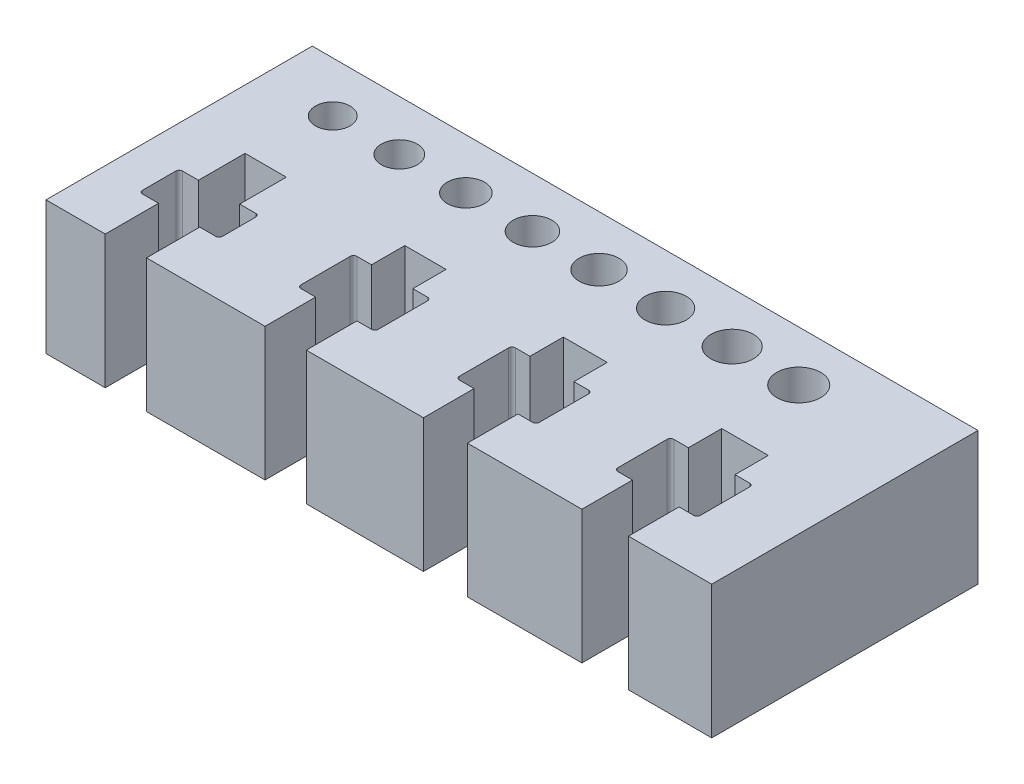
SolidWorks part; units mm, degrees
ref_plane "Front Plane" through (0, 0, 0) normal (0, 0, 1) x (1, 0, 0)
ref_plane "Top Plane" through (0, 0, 0) normal (0, 1, 0) x (1, 0, 0)
ref_plane "Right Plane" through (0, 0, 0) normal (1, 0, 0) x (0, 0, -1)
sketch "Sketch2" plane through (0, 0, 0) normal (0, 1, 0) x (1, 0, 0)
  line L1 (-25, 10) -> (25, 10)
  line L2 (-25, 10) -> (-25, -10)
  line L3 (-25, -10) -> (25, -10)
  line L4 (25, 10) -> (25, -10)
  line L5 (-25, 10) -> (25, -10) construction
  line L6 (-25, -10) -> (25, 10) construction
  point P0 (0, 0)
  dimension "D1" = 50
  dimension "D2" = 20
extrude "Boss-Extrude1" add sketch "Sketch2" along normal blind 10
sketch "Sketch3" plane through (0, 10, 0) normal (0, 1, 0) x (1, 0, 0)
  line L0 (5, -10) -> (5, 0.5) construction
  line L1 (-25, -10) -> (25, -10) construction
  line L2 (6.65, 0.5) -> (3.35, 0.5) construction
  line L3 (3.35, 0.5) -> (3.35, -10) construction
  line L4 (6.65, -10) -> (3.35, -10)
  line L5 (3.35, -10) -> (3.35, -6.2)
  line L6 (3.35, -6.2) -> (2.25, -6.2)
  line L7 (2, -5.95) -> (2, -2.25)
  line L8 (2.25, -2) -> (3.35, -2)
  line L9 (3.35, -2) -> (3.35, 0.5)
  line L10 (3.35, 0.5) -> (6.65, 0.5)
  line L11 (-25, 10) -> (-25, -10) construction
  line L12 (6.65, 0.5) -> (6.65, -10) construction
  line L13 (6.65, -2) -> (6.65, 0.5)
  line L14 (7.75, -2) -> (6.65, -2)
  line L15 (8, -5.95) -> (8, -2.25)
  line L16 (6.65, -6.2) -> (7.75, -6.2)
  line L17 (6.65, -10) -> (6.65, -6.2)
  line L18 (17, -10) -> (17, 0.5) construction
  line L19 (15.25, 0.5) -> (18.75, 0.5)
  line L20 (15.25, 0.5) -> (15.25, -10) construction
  line L21 (15.25, -10) -> (18.75, -10)
  line L22 (15.25, -10) -> (15.25, -6.2)
  line L23 (15.25, -6.2) -> (14.15, -6.2)
  line L24 (13.9, -5.95) -> (13.9, -2.25)
  line L25 (14.15, -2) -> (15.25, -2)
  line L26 (15.25, -2) -> (15.25, 0.5)
  line L27 (18.75, 0.5) -> (18.75, -10) construction
  line L28 (18.75, -2) -> (18.75, 0.5)
  line L29 (19.85, -2) -> (18.75, -2)
  line L30 (20.1, -5.95) -> (20.1, -2.25)
  line L31 (18.75, -6.2) -> (19.85, -6.2)
  line L32 (18.75, -10) -> (18.75, -6.2)
  line L33 (-7, -10) -> (-7, 0.5) construction
  line L34 (-8.55, 0.5) -> (-5.45, 0.5)
  line L35 (-8.55, 0.5) -> (-8.55, -10) construction
  line L36 (-8.55, -10) -> (-5.45, -10)
  line L37 (-8.55, -10) -> (-8.55, -6.2)
  line L38 (-8.55, -6.2) -> (-9.65, -6.2)
  line L39 (-9.9, -5.95) -> (-9.9, -2.25)
  line L40 (-9.65, -2) -> (-8.55, -2)
  line L41 (-8.55, -2) -> (-8.55, 0.5)
  line L42 (-5.45, 0.5) -> (-5.45, -10) construction
  line L43 (-5.45, -2) -> (-5.45, 0.5)
  line L44 (-4.35, -2) -> (-5.45, -2)
  line L45 (-4.1, -5.95) -> (-4.1, -2.25)
  line L46 (-5.45, -6.2) -> (-4.35, -6.2)
  line L47 (-5.45, -10) -> (-5.45, -6.2)
  line L48 (-19, -10) -> (-19, 0.5) construction
  line L49 (-20.55, 0.5) -> (-17.45, 0.5)
  line L50 (-20.55, 0.5) -> (-20.55, -10) construction
  line L51 (-20.55, -10) -> (-17.45, -10)
  line L52 (-20.55, -10) -> (-20.55, -6)
  line L53 (-20.55, -6) -> (-21.75, -6)
  line L54 (-22, -5.75) -> (-22, -3.25)
  line L55 (-21.75, -3) -> (-20.55, -3)
  line L56 (-20.55, -3) -> (-20.55, 0.5)
  line L57 (-17.45, 0.5) -> (-17.45, -10) construction
  line L58 (-17.45, -3) -> (-17.45, 0.5)
  line L59 (-16.25, -3) -> (-17.45, -3)
  line L60 (-16, -5.75) -> (-16, -3.25)
  line L61 (-17.45, -6) -> (-16.25, -6)
  line L62 (-17.45, -10) -> (-17.45, -6)
  line L63 (-25, 6.2223) -> (25, 6.2223) construction
  line L64 (25, -10) -> (25, 10) construction
  arc A0 (2.25, -6.2) -> (2, -5.95) centre (2.25, -5.95) cw
  arc A1 (2, -2.25) -> (2.25, -2) centre (2.25, -2.25) cw
  arc A2 (8, -2.25) -> (7.75, -2) centre (7.75, -2.25) ccw
  arc A3 (7.75, -6.2) -> (8, -5.95) centre (7.75, -5.95) ccw
  arc A4 (14.15, -6.2) -> (13.9, -5.95) centre (14.15, -5.95) cw
  arc A5 (13.9, -2.25) -> (14.15, -2) centre (14.15, -2.25) cw
  arc A6 (20.1, -2.25) -> (19.85, -2) centre (19.85, -2.25) ccw
  arc A7 (19.85, -6.2) -> (20.1, -5.95) centre (19.85, -5.95) ccw
  arc A8 (-9.65, -6.2) -> (-9.9, -5.95) centre (-9.65, -5.95) cw
  arc A9 (-9.9, -2.25) -> (-9.65, -2) centre (-9.65, -2.25) cw
  arc A10 (-4.1, -2.25) -> (-4.35, -2) centre (-4.35, -2.25) ccw
  arc A11 (-4.35, -6.2) -> (-4.1, -5.95) centre (-4.35, -5.95) ccw
  arc A12 (-21.75, -6) -> (-22, -5.75) centre (-21.75, -5.75) cw
  arc A13 (-22, -3.25) -> (-21.75, -3) centre (-21.75, -3.25) cw
  arc A14 (-16, -3.25) -> (-16.25, -3) centre (-16.25, -3.25) ccw
  arc A15 (-16.25, -6) -> (-16, -5.75) centre (-16.25, -5.75) ccw
  circle A16 centre (-19.6857, 6.2223) radius 1.3
  circle A17 centre (-14.6857, 6.2223) radius 1.35
  circle A18 centre (-9.6857, 6.2223) radius 1.4
  circle A19 centre (-4.6857, 6.2223) radius 1.45
  circle A20 centre (0.3143, 6.2223) radius 1.5
  circle A21 centre (5.3143, 6.2223) radius 1.55
  circle A22 centre (10.3143, 6.2223) radius 1.6
  circle A23 centre (15.3143, 6.2223) radius 1.65
  point P14 (2, -6.2)
  point P17 (2, -2)
  point P28 (8, -2)
  point P29 (8, -6.2)
  dimension "D7" = 0.25
  dimension "D10" = 0.25
  dimension "D15" = 0.25
  dimension "D22" = 0.25
  dimension "D30" = 2.6
  dimension "D29" = 2.7
  dimension "D31" = 2.8
  dimension "D32" = 2.9
  dimension "D33" = 3
  dimension "D34" = 3.1
  dimension "D35" = 3.2
  dimension "D36" = 3.3
  dimension "D1" = 10.5
  dimension "D2" = 4.2
  dimension "D3" = 3
  dimension "D4" = 1.65
  dimension "D5" = 30
  dimension "D6" = 8
  dimension "D12" = 12
  dimension "D8" = 1.75
  dimension "D9" = 3.1
  dimension "D11" = 4.2
  dimension "D13" = 8
  dimension "D14" = 10.5
  dimension "D16" = 1.55
  dimension "D17" = 4.2
  dimension "D18" = 10.5
  dimension "D19" = 12
  dimension "D20" = 2.9
  dimension "D21" = 8
  dimension "D23" = 3
  dimension "D24" = 10.5
  dimension "D25" = 3
  dimension "D26" = 7
  dimension "D27" = 1.55
  dimension "D28" = 12
extrude "Cut-Extrude1" cut sketch "Sketch3" against normal through all
equation "\"X-ROD-SPACING\"=45"
equation "\"Y-ROD-SPACING\"=75"
equation "\"Z-ROD-SPACING\"=17.5"
equation "\"Y-BED-OFFSET\"=2"
equation "\"Y-BED-ROD-INSET\"=3.5"
equation "\"Y-BED-SCREW-SPACING\"=209"
equation "\"Y-BED-SCREW-CUTOUT-SLOT-HEIGHT\"=2"
equation "\"T-SLOT-NUT-FILLET-RADIUS\"=0.25"
equation "\"T-SLOT-SCREW-SHAFT-RADIUS\"=1.75"
equation "\"T-SLOT-SCREW-SHAFT-CUTOUT-LENGTH\"=10.5"
equation "\"T-SLOT-NUT-DEPTH\"=4.2"
equation "\"T-SLOT-NUT-WIDTH\"=3"
equation "\"T-SLOT-NUT-END-DISTANCE\"=8"
equation "\"ACRYLIC-THICKNESS\"=10"
equation "\"ACRYLIC-THICKNESS2\"=4.5"
equation "\"ACRYLIC-TAB-CUTOUT-SIZE\"=\"ACRYLIC-THICKNESS\"+\"ACRYLIC-TAB-TOLERANCE\"*2"
equation "\"ACRYLIC-TAB-TOLERANCE\"=.1"
equation "\"ACRYLIC-TAB-WIDTH\"=\"ACRYLIC-THICKNESS\""
equation "\"ACRYLIC-M3-HOLE\"=3.1"
equation "\"SMOOTHROD-CAP-SCREW-DISTANCE\"=20"
equation "\"FRAME-WIDTH-INNER\"=370"
equation "\"NEMA17-HOLE-SPACING\"=31"
equation "\"NEMA17-CENTRAL-CUTOUT\"=22.5"
equation "\"Z-BRACKET-REACH\"=55"
equation "\"Z-ROD-INSET\"=16"
equation "\"TOP-BRACKET-SPACING\"=40"
equation "\"SMOOTHROD-X-LENGTH\"=350"
equation "\"SMOOTHROD-Y-LENGTH\"=350"
equation "\"SMOOTHROD-Z-LENGTH\"=350"
equation "\"SMOOTHROD-TIGHTENING-HEADROOM\"=.25"
equation "\"LEADSCREW-Z-LENGTH\"=300"
equation "\"SCREW-LENGTH-FRAME\"=\"ACRYLIC-THICKNESS\" + 10"
equation "\"SCREW-LENGTH-MOTOR\"=\"ACRYLIC-THICKNESS\" + 5"
equation "\"SCREW-LENGTH-EXTRUDER\"=28"
equation "\"SCREW-HEAD-RADIUS\"=6"
equation "\"PRINTED-M3-HOLE\"=3.5"
equation "\"PRINTED-X-SMOOTHROD-DIAMETER\"=8.2"
equation "\"PRINTED-X-SMOOTHROD-CUTOUT\"=10"
equation "\"PRINTED-X-BASE-HEIGHT\"=10"
equation "\"PRINTED-LM8UU-CUTOUT-SIZE\"=15.25"
equation "\"PRINTED-LM8UU-CUTOUT-LENGTH\"=24.5"
equation "\"PRINTED-X-IDLER-HEIGHT\"=16"
equation "\"PRINTED-M3-NUT-AF\"=6.25"
equation "\"PSU-MOUNTING-WIDTH\"=95"
equation "\"PSU-MOUNTING-HEIGHT\"=177"
equation "\"Y-BELT-TO-ROD-DISTANCE\"=20"
equation "\"SPOOL-HOLDER-ROD-SPACING\"=150"
equation "\"ACRYLIC-X-CARRIAGE-WIDTH\"=55"
equation "\"ACRYLIC-X-CARRIAGE-HEIGHT\"=75"
equation "\"ACRYLIC-X-CARRIAGE-LM8UU-CUTOUT-WIDTH\"=24.25"
equation "\"ACRYLIC-X-CARRIAGE-LM8UU-CUTOUT-HEIGHT\"=11.5"
equation "\"ACRYLIC-X-CARRIAGE-SCREW-SPACING-X\"=15"
equation "\"ACRYLIC-X-CARRIAGE-SCREW-SPACING-Y\"=33"
equation "\"ACRYLIC-X-CARRIAGE-CENTER-TAB-SPACING\"=14"
equation "\"ACRYLIC-X-CARRIAGE-EXTRUDER-OFFSET\"=26"
equation "\"ACRYLIC-X-CARRIAGE-EXTRUDER-ANGLE\"=90"
equation "\"ACRYLIC-X-CARRIAGE-EXTRUDER-SHELF-DEPTH\"=\"ACRYLIC-X-CARRIAGE-EXTRUDER-OFFSET\" + 28"
equation "\"ACRYLIC-X-CARRIAGE-EXTRUDER-BRACE-SPACING\"=23"
equation "\"ACRYLIC-X-CARRIAGE-EXTRUDER-BRACE-TAB-OFFSET\"=20"
equation "\"ACRYLIC-X-CARRIAGE-EXTRUDER-BRACE-HEIGHT\"=35"
equation "\"ACRYLIC-X-CARRIAGE-EXTRUDER-BRACE-SCREW-SPACING\"=22"
equation "\"ACRYLIC-X-CARRIAGE-DUAL-WIDTH-MULTIPLIER\"=1.65"
equation "\"ACRYLIC-X-CARRIAGE-DUAL-HOTEND-SPACING\"=42"
equation "\"ACRYLIC-X-CARRIAGE-DUAL-WIDTH\"=75"
equation "\"ACRYLIC-X-CARRIAGE-DUAL-FAN-OFFSET\"=52"
equation "\"ACRYLIC-X-CARRIAGE-DUAL-FAN-HEIGHT\"=20"
equation "\"ACRYLIC-X-CARRIAGE-DUAL-HOTEND-SEPARATION\"=36"
equation "\"ACRYLIC-X-CARRIAGE-DUAL-MOUNT-PLATE-DEPTH\"=75"
equation "\"ACRYLIC-X-CARRIAGE-DUAL-MOUNT-BRACE-WIDTH\"=33"
equation "\"ACRYLIC-X-CARRIAGE-DUAL-MOUNT-SCREW-WIDTH\"=40"
equation "\"BLOWER-FAN-WIDTH\"=15"
equation "\"D1@Boss-Extrude1\"=\"ACRYLIC-THICKNESS\""
equation "\"D1@Sketch3\"=\"T-SLOT-SCREW-SHAFT-CUTOUT-LENGTH\""
equation "\"D2@Sketch3\"=\"T-SLOT-NUT-DEPTH\""
equation "\"D3@Sketch3\"=\"T-SLOT-NUT-WIDTH\""
equation "\"D6@Sketch3\"=\"T-SLOT-NUT-END-DISTANCE\""
equation "\"D7@Sketch3\"=\"T-SLOT-NUT-FILLET-RADIUS\""
